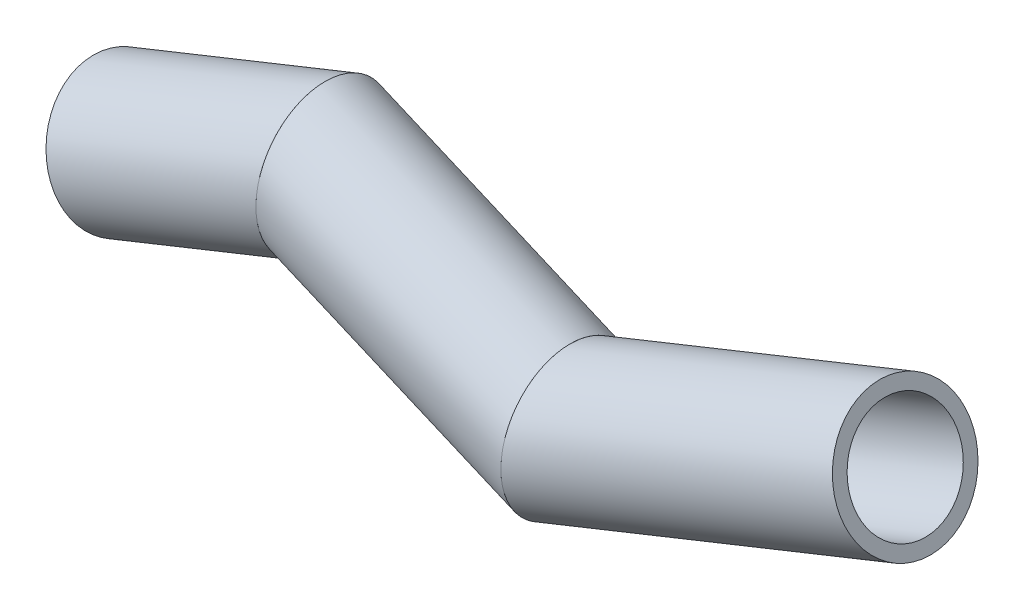
SolidWorks part; units mm, degrees
ref_plane "Front Plane" through (0, 0, 0) normal (0, 0, 1) x (1, 0, 0)
ref_plane "Top Plane" through (0, 0, 0) normal (0, 1, 0) x (1, 0, 0)
ref_plane "Right Plane" through (0, 0, 0) normal (1, 0, 0) x (0, 0, -1)
sketch "Sketch2" plane through (0, 0, 0) normal (0, 0, 1) x (1, 0, 0)
  line L0 (-71.9231, -13.9051) -> (-21.6728, 6.2333)
  line L1 (-21.6728, 6.2333) -> (38.2732, -19.4112)
  line L2 (38.2732, -19.4112) -> (120.5129, 13.5475)
ref_plane "Plane1" through (-71.9231, -13.9051, 0) normal (0.9282, 0.372, 0) x (0, 0, -1)
other "Pipe 1.0 SCH 40(1)"
ref_plane "Plane2" through (-71.9231, -13.9051, 0) normal (0.9282, 0.372, 0) x (-0.372, 0.9282, 0)
sketch "Sketch13" plane through (-71.9231, -13.9051, 0) normal (0.9282, 0.372, 0) x (-0.372, 0.9282, 0)
  circle A0 centre (0, 0) radius 13.3223
  circle A1 centre (0, 0) radius 16.7005
  circle A2 centre (0, 0) radius 12.7 construction
  point P5 (0, 16.7005)
  point P6 (0, -16.7005)
  point P7 (-16.7005, 0)
  point P8 (16.7005, 0)
  point P9 (0, 0)
  dimension "In_dia" = 26.6446
  dimension "Out_dia" = 33.401
  dimension "D1" = 25.4
